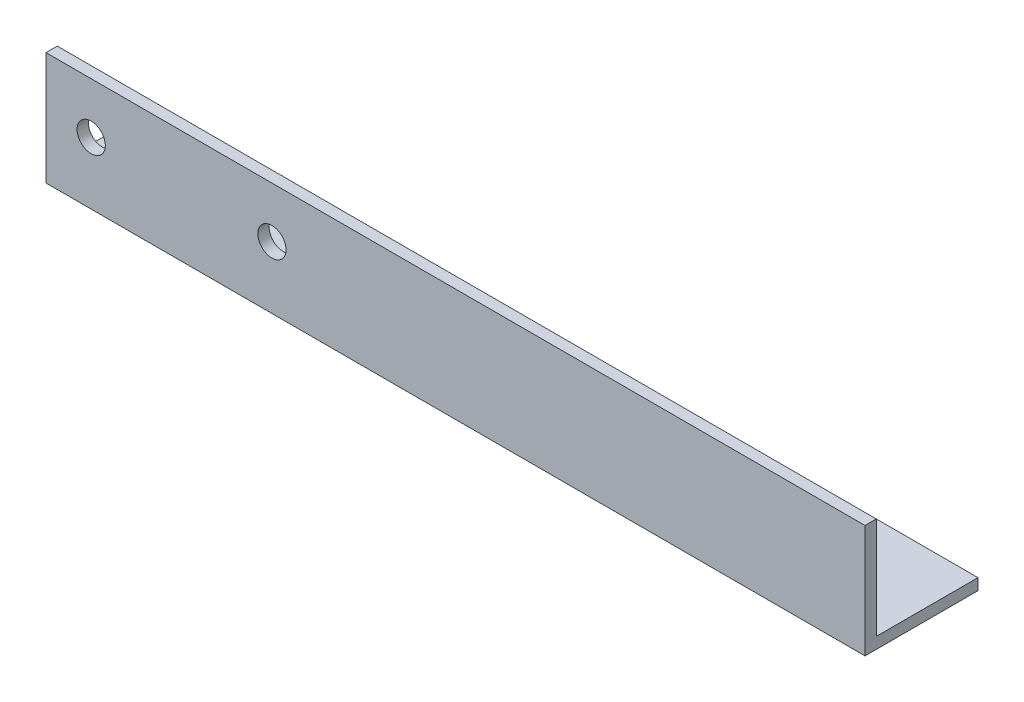
SolidWorks part; units mm, degrees
ref_plane "Front Plane" through (0, 0, 0) normal (0, 0, 1) x (1, 0, 0)
ref_plane "Top Plane" through (0, 0, 0) normal (0, 1, 0) x (1, 0, 0)
ref_plane "Right Plane" through (0, 0, 0) normal (1, 0, 0) x (0, 0, -1)
sketch "Sketch1" plane through (0, 0, 0) normal (1, 0, 0) x (0, 0, -1)
  line L0 (0, 20) -> (0, 0)
  line L1 (0, 0) -> (20, 0)
  line L2 (20, 0) -> (20, 2)
  line L3 (20, 2) -> (2, 2)
  line L4 (2, 2) -> (2, 20)
  line L5 (2, 20) -> (0, 20)
  dimension "D1" = 20
  dimension "D2" = 20
  dimension "D3" = 2
  dimension "D4" = 2
extrude "Boss-Extrude1" add sketch "Sketch1" along normal blind 145
sketch "Sketch2" plane through (0, 0, -2) normal (0, 0, -1) x (-1, 0, 0)
  line L0 (-145, 20) -> (0, 20) construction
  line L1 (0, 2) -> (0, 20) construction
  circle A0 centre (-8, 11) radius 2.5
  circle A1 centre (-40, 11) radius 2.5
  dimension "D3" = 5
  dimension "D4" = 5
  dimension "D1" = 9
  dimension "D2" = 8
  dimension "D5" = 40
extrude "Cut-Extrude1" cut sketch "Sketch2" against normal blind 2
